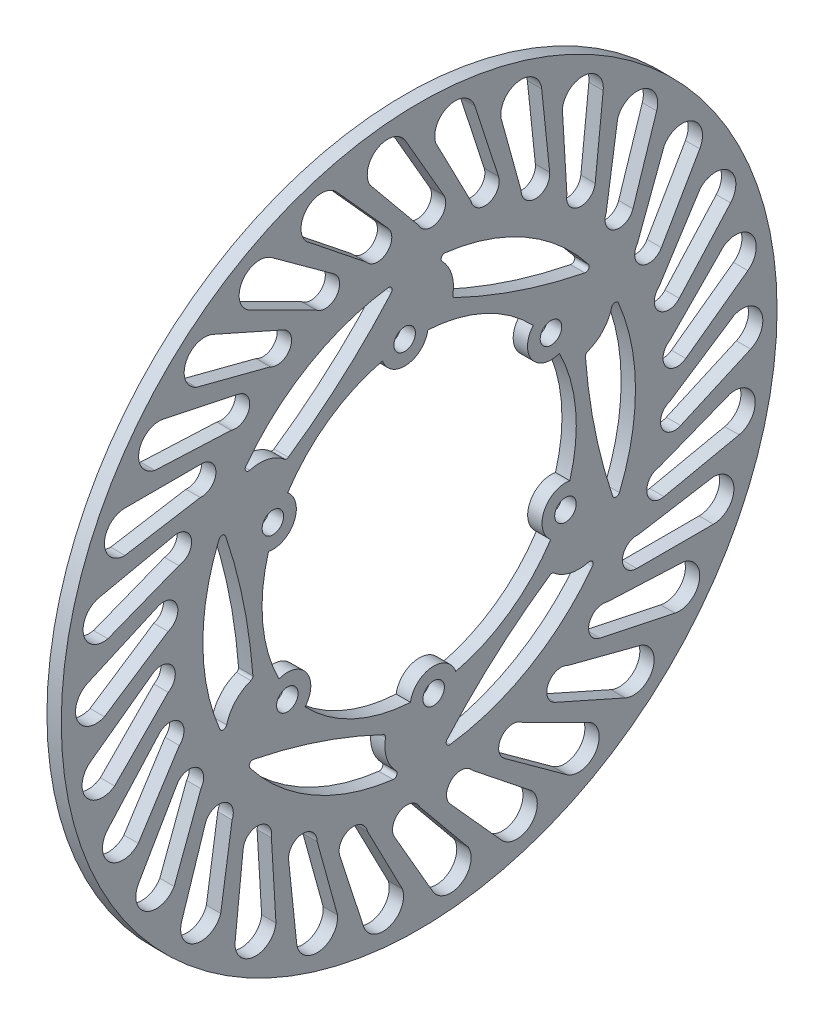
SolidWorks part; units mm, degrees
material "Gray Cast Iron"
ref_plane "Front Plane" through (0, 0, 0) normal (0, 0, 1) x (1, 0, 0)
ref_plane "Top Plane" through (0, 0, 0) normal (0, 1, 0) x (1, 0, 0)
ref_plane "Right Plane" through (0, 0, 0) normal (1, 0, 0) x (0, 0, -1)
sketch "Sketch1" plane through (0, 0, 0) normal (1, 0, 0) x (0, 0, -1)
  line L40 (68.3953, 55.3362) -> (60.9105, 35.4074)
  line L41 (78.3278, 49.6298) -> (67.626, 31.0928)
  line L42 (66.2976, 64.8306) -> (59.6837, 44.4737)
  line L43 (55.3957, 68.3472) -> (52.2179, 47.2977)
  line L44 (78.4057, 39.9067) -> (66.9411, 21.9696)
  line L45 (86.9347, 32.2599) -> (72.6128, 16.3531)
  line L46 (84.9894, 22.7332) -> (70.046, 7.5716)
  line L47 (91.7422, 13.4802) -> (74.426, 0.8987)
  line L48 (87.8586, 4.5661) -> (70.0895, -7.1572)
  line L49 (92.5401, -5.8887) -> (72.9864, -14.595)
  line L50 (86.888, -13.8006) -> (67.0698, -21.5733)
  line L51 (89.2935, -25.0002) -> (68.3569, -29.4509)
  line L52 (82.12, -31.5641) -> (61.1188, -35.0465)
  line L53 (82.1443, -43.0191) -> (60.74, -43.0196)
  line L54 (73.7629, -47.9481) -> (52.4966, -46.988)
  line L55 (71.4051, -59.1578) -> (50.4684, -54.7081)
  line L56 (62.182, -62.2365) -> (41.58, -56.8759)
  line L57 (57.5451, -72.7111) -> (37.991, -64.0056)
  line L58 (47.8834, -73.8049) -> (28.8462, -64.278)
  line L59 (41.1701, -83.0865) -> (23.8533, -70.5057)
  line L60 (31.4921, -82.1477) -> (14.8516, -68.8709)
  line L61 (22.9957, -89.8306) -> (8.6731, -73.9244)
  line L62 (13.7245, -86.9002) -> (0.208, -70.4538)
  line L63 (3.8163, -92.6487) -> (-6.8863, -74.1122)
  line L64 (-4.643, -87.8547) -> (-14.4447, -68.9575)
  line L65 (-15.5299, -91.4176) -> (-22.1446, -71.061)
  line L66 (-22.8076, -84.9696) -> (-28.4662, -64.4474)
  line L67 (-34.1973, -86.1911) -> (-36.4351, -64.9041)
  line L68 (-39.9754, -78.3708) -> (-41.2435, -57.1206)
  line L69 (-51.3702, -77.1977) -> (-49.1333, -55.9105)
  line L70 (-55.3961, -68.3469) -> (-52.2183, -47.2975)
  line L71 (-66.298, -64.8303) -> (-59.6841, -44.4734)
  line L72 (-68.3957, -55.3359) -> (-60.911, -35.4071)
  line L73 (-78.3282, -49.6295) -> (-67.6264, -31.0926)
  line L74 (-78.4061, -39.9065) -> (-66.9415, -21.9693)
  line L75 (-86.9351, -32.2597) -> (-72.6132, -16.3528)
  line L76 (-84.9898, -22.7329) -> (-70.0464, -7.5714)
  line L77 (-91.7426, -13.4799) -> (-74.4264, -0.8984)
  line L78 (-87.8591, -4.5658) -> (-70.0899, 7.1575)
  line L79 (-92.5405, 5.8889) -> (-72.9868, 14.5953)
  line L80 (-86.8884, 13.8009) -> (-67.0702, 21.5736)
  line L81 (-89.2939, 25.0005) -> (-68.3574, 29.4511)
  line L82 (-82.1204, 31.5644) -> (-61.1192, 35.0468)
  line L83 (-82.1447, 43.0193) -> (-60.7404, 43.0198)
  line L84 (-73.7633, 47.9483) -> (-52.497, 46.9882)
  line L85 (-71.4055, 59.1581) -> (-50.4688, 54.7083)
  line L86 (-62.1824, 62.2368) -> (-41.5804, 56.8761)
  line L87 (-57.5455, 72.7113) -> (-37.9914, 64.0058)
  line L88 (-47.8838, 73.8052) -> (-28.8466, 64.2783)
  line L89 (-41.1705, 83.0868) -> (-23.8537, 70.506)
  line L90 (-31.4925, 82.1479) -> (-14.8521, 68.8711)
  line L91 (-22.9961, 89.8309) -> (-8.6735, 73.9247)
  line L92 (-13.7249, 86.9004) -> (-0.2084, 70.454)
  line L93 (-3.8167, 92.649) -> (6.8858, 74.1125)
  line L94 (4.6426, 87.855) -> (14.4443, 68.9577)
  line L95 (15.5294, 91.4179) -> (22.1442, 71.0613)
  line L96 (22.8072, 84.9698) -> (28.4658, 64.4476)
  line L97 (34.1969, 86.1914) -> (36.4347, 64.9043)
  line L98 (39.975, 78.3711) -> (41.2431, 57.1209)
  line L99 (51.3698, 77.1979) -> (49.1329, 55.9108)
  circle A0 centre (0, 0) radius 99.9066
  arc A1 (42.051, -12.4701) -> (39.1395, 19.7962) centre (0, 0) ccw
  circle A2 centre (-4.0441, 44.8179) radius 3
  circle A3 centre (36.7914, 25.9112) radius 3
  circle A4 centre (40.8355, -18.9067) radius 3
  circle A5 centre (4.0441, -44.8179) radius 3
  circle A6 centre (-36.7914, -25.9112) radius 3
  circle A7 centre (-40.8355, 18.9067) radius 3
  arc A72 (67.626, 31.0928) -> (60.9105, 35.4074) centre (64.1618, 33.0843) cw
  arc A73 (78.3278, 49.6298) -> (68.3953, 55.3362) centre (73.3616, 52.483) ccw
  arc A74 (66.2976, 64.8306) -> (55.3957, 68.3472) centre (60.8466, 66.5889) ccw
  arc A75 (59.6837, 44.4737) -> (52.2179, 47.2977) centre (55.8811, 45.7014) cw
  arc A76 (72.6128, 16.3531) -> (66.9411, 21.9696) centre (69.6383, 19.0213) cw
  arc A77 (86.9347, 32.2599) -> (78.4057, 39.9067) centre (82.6702, 36.0833) ccw
  arc A78 (74.426, 0.8987) -> (70.046, 7.5716) centre (72.0712, 4.127) cw
  arc A79 (91.7422, 13.4802) -> (84.9894, 22.7332) centre (88.3658, 18.1067) ccw
  arc A80 (72.9864, -14.595) -> (70.0895, -7.1572) centre (71.3543, -10.9477) cw
  arc A81 (92.5401, -5.8887) -> (87.8586, 4.5661) centre (90.1994, -0.6613) ccw
  arc A82 (68.3569, -29.4509) -> (67.0698, -21.5733) centre (67.5189, -25.5439) cw
  arc A83 (89.2935, -25.0002) -> (86.888, -13.8006) centre (88.0908, -19.4004) ccw
  arc A84 (60.74, -43.0196) -> (61.1188, -35.0465) centre (60.7325, -39.0237) cw
  arc A85 (82.1443, -43.0191) -> (82.12, -31.5641) centre (82.1322, -37.2916) ccw
  arc A86 (50.4684, -54.7081) -> (52.4966, -46.988) centre (51.2919, -50.798) cw
  arc A87 (71.4051, -59.1578) -> (73.7629, -47.9481) centre (72.584, -53.553) ccw
  arc A88 (37.991, -64.0056) -> (41.58, -56.8759) centre (39.6095, -60.3521) cw
  arc A89 (57.5451, -72.7111) -> (62.182, -62.2365) centre (59.8635, -67.4738) ccw
  arc A90 (23.8533, -70.5057) -> (28.8462, -64.278) centre (26.196, -67.2686) cw
  arc A91 (41.1701, -83.0865) -> (47.8834, -73.8049) centre (44.5267, -78.4457) ccw
  arc A92 (8.6731, -73.9244) -> (14.8516, -68.8709) centre (11.6376, -71.2451) cw
  arc A93 (22.9957, -89.8306) -> (31.4921, -82.1477) centre (27.2439, -85.9891) ccw
  arc A94 (-6.8863, -74.1122) -> (0.208, -70.4538) centre (-3.4294, -72.1079) cw
  arc A95 (3.8163, -92.6487) -> (13.7245, -86.9002) centre (8.7704, -89.7745) ccw
  arc A96 (-22.1446, -71.061) -> (-14.4447, -68.9575) centre (-18.3466, -69.8192) cw
  arc A97 (-15.5299, -91.4176) -> (-4.643, -87.8547) centre (-10.0864, -89.6362) ccw
  arc A98 (-36.4351, -64.9041) -> (-28.4662, -64.4474) centre (-32.4619, -64.479) cw
  arc A99 (-34.1973, -86.1911) -> (-22.8076, -84.9696) centre (-28.5025, -85.5804) ccw
  arc A100 (-49.1333, -55.9105) -> (-41.2435, -57.1206) centre (-45.1585, -56.3208) cw
  arc A101 (-51.3702, -77.1977) -> (-39.9754, -78.3708) centre (-45.6728, -77.7843) ccw
  arc A102 (-59.6841, -44.4734) -> (-52.2183, -47.2975) centre (-55.8815, -45.7011) cw
  arc A103 (-66.298, -64.8303) -> (-55.3961, -68.3469) centre (-60.847, -66.5886) ccw
  arc A104 (-67.6264, -31.0926) -> (-60.911, -35.4071) centre (-64.1622, -33.0841) cw
  arc A105 (-78.3282, -49.6295) -> (-68.3957, -55.3359) centre (-73.362, -52.4827) ccw
  arc A106 (-72.6132, -16.3528) -> (-66.9415, -21.9693) centre (-69.6387, -19.0211) cw
  arc A107 (-86.9351, -32.2597) -> (-78.4061, -39.9065) centre (-82.6706, -36.0831) ccw
  arc A108 (-74.4264, -0.8984) -> (-70.0464, -7.5714) centre (-72.0717, -4.1268) cw
  arc A109 (-91.7426, -13.4799) -> (-84.9898, -22.7329) centre (-88.3662, -18.1064) ccw
  arc A110 (-72.9868, 14.5953) -> (-70.0899, 7.1575) centre (-71.3547, 10.9479) cw
  arc A111 (-92.5405, 5.8889) -> (-87.8591, -4.5658) centre (-90.1998, 0.6616) ccw
  arc A112 (-68.3574, 29.4511) -> (-67.0702, 21.5736) centre (-67.5193, 25.5441) cw
  arc A113 (-89.2939, 25.0005) -> (-86.8884, 13.8009) centre (-88.0912, 19.4007) ccw
  arc A114 (-60.7404, 43.0198) -> (-61.1192, 35.0468) centre (-60.733, 39.0239) cw
  arc A115 (-82.1447, 43.0193) -> (-82.1204, 31.5644) centre (-82.1326, 37.2919) ccw
  arc A116 (-50.4688, 54.7083) -> (-52.497, 46.9882) centre (-51.2923, 50.7982) cw
  arc A117 (-71.4055, 59.1581) -> (-73.7633, 47.9483) centre (-72.5844, 53.5532) ccw
  arc A118 (-37.9914, 64.0058) -> (-41.5804, 56.8761) centre (-39.6099, 60.3524) cw
  arc A119 (-57.5455, 72.7113) -> (-62.1824, 62.2368) centre (-59.8639, 67.4741) ccw
  arc A144 (42.051, -12.4701) -> (36.7137, -23.9977) centre (40.8355, -18.9067) ccw
  arc A145 (10.226, -42.6523) -> (-2.4257, -43.7939) centre (4.0441, -44.8179) ccw
  arc A146 (-31.8249, -30.1821) -> (-39.1395, -19.7962) centre (-36.7914, -25.9112) ccw
  arc A147 (-42.051, 12.4701) -> (-36.7137, 23.9977) centre (-40.8355, 18.9067) ccw
  arc A148 (-10.226, 42.6523) -> (2.4257, 43.7939) centre (-4.0441, 44.8179) ccw
  arc A149 (31.8249, 30.1821) -> (39.1395, 19.7962) centre (36.7914, 25.9112) ccw
  arc A150 (10.226, -42.6523) -> (36.7137, -23.9977) centre (0, 0) ccw
  arc A151 (-31.8249, -30.1821) -> (-2.4257, -43.7939) centre (0, 0) ccw
  arc A152 (-42.051, 12.4701) -> (-39.1395, -19.7962) centre (0, 0) ccw
  arc A153 (-10.226, 42.6523) -> (-36.7137, 23.9977) centre (0, 0) ccw
  arc A154 (31.8249, 30.1821) -> (2.4257, 43.7939) centre (0, 0) ccw
  arc A155 (-23.8537, 70.506) -> (-28.8466, 64.2783) centre (-26.1964, 67.2689) cw
  arc A156 (-41.1705, 83.0868) -> (-47.8838, 73.8052) centre (-44.5272, 78.446) ccw
  arc A157 (-8.6735, 73.9247) -> (-14.8521, 68.8711) centre (-11.638, 71.2454) cw
  arc A158 (-22.9961, 89.8309) -> (-31.4925, 82.1479) centre (-27.2443, 85.9894) ccw
  arc A159 (6.8858, 74.1125) -> (-0.2084, 70.454) centre (3.429, 72.1081) cw
  arc A160 (-3.8167, 92.649) -> (-13.7249, 86.9004) centre (-8.7708, 89.7747) ccw
  arc A161 (22.1442, 71.0613) -> (14.4443, 68.9577) centre (18.3462, 69.8194) cw
  arc A162 (15.5294, 91.4179) -> (4.6426, 87.855) centre (10.086, 89.6364) ccw
  arc A163 (36.4347, 64.9043) -> (28.4658, 64.4476) centre (32.4615, 64.4793) cw
  arc A168 (34.1969, 86.1914) -> (22.8072, 84.9698) centre (28.5021, 85.5806) ccw
  arc A173 (49.1329, 55.9108) -> (41.2431, 57.1209) centre (45.1581, 56.3211) cw
  arc A178 (51.3698, 77.1979) -> (39.975, 78.3711) centre (45.6724, 77.7845) ccw
  arc A200 (-7.7896, 57.8859) -> (-36.5325, 32.4972) centre (-123.3086, 159.7023) cw
  arc A201 (-47.3041, 34.7453) -> (-37.5781, 32.5523) centre (-44.5369, 24.3543) cw
  arc A202 (-8.6724, 59.5383) -> (-48.3606, 36.3128) centre (-0.7718, 0.515) ccw
  arc A211 (-36.5325, 32.4972) -> (-37.5781, 32.5523) centre (-37.0192, 33.2107) cw
  arc A230 (-48.3606, 36.3128) -> (-47.3041, 34.7453) centre (-47.5615, 35.7116) ccw
  arc A231 (-8.6724, 59.5383) -> (-7.7896, 57.8859) centre (-8.5398, 58.5472) cw
  arc A232 (46.2359, 35.6889) -> (9.8772, 47.8867) centre (76.6519, 186.6396) cw
  arc A233 (47.2255, 37.2797) -> (46.2359, 35.6889) centre (46.4334, 36.6692) cw
  arc A234 (9.8772, 47.8867) -> (9.402, 48.8197) centre (10.2517, 48.6649) cw
  arc A235 (6.4383, 58.3392) -> (9.402, 48.8197) centre (-1.177, 50.7472) cw
  arc A236 (7.2675, 60.0379) -> (6.4383, 58.3392) centre (7.1465, 59.0453) ccw
  arc A237 (47.2255, 37.2797) -> (7.2675, 60.0379) centre (0.0601, 0.9259) ccw
  arc A238 (54.0255, -22.197) -> (46.4097, 15.3894) centre (199.9605, 26.9373) cw
  arc A239 (55.8979, -22.2586) -> (54.0255, -22.197) centre (54.9732, -21.8779) cw
  arc A240 (46.4097, 15.3894) -> (46.9801, 16.2674) centre (47.2709, 15.4542) cw
  arc A241 (53.7424, 23.5939) -> (46.9801, 16.2674) centre (43.3598, 26.3929) cw
  arc A242 (55.6281, 23.7251) -> (53.7424, 23.5939) centre (54.7079, 23.3336) ccw
  arc A243 (55.8979, -22.2586) -> (55.6281, 23.7251) centre (0.8319, 0.4109) ccw
  arc A244 (7.7896, -57.8859) -> (36.5325, -32.4972) centre (123.3086, -159.7023) cw
  arc A245 (8.6724, -59.5383) -> (7.7896, -57.8859) centre (8.5398, -58.5472) cw
  arc A246 (36.5325, -32.4972) -> (37.5781, -32.5523) centre (37.0192, -33.2107) cw
  arc A247 (47.3041, -34.7453) -> (37.5781, -32.5523) centre (44.5369, -24.3543) cw
  arc A248 (48.3606, -36.3128) -> (47.3041, -34.7453) centre (47.5615, -35.7116) ccw
  arc A249 (8.6724, -59.5383) -> (48.3606, -36.3128) centre (0.7718, -0.515) ccw
  arc A250 (-46.2359, -35.6889) -> (-9.8772, -47.8867) centre (-76.6519, -186.6396) cw
  arc A251 (-47.2255, -37.2797) -> (-46.2359, -35.6889) centre (-46.4334, -36.6692) cw
  arc A252 (-9.8772, -47.8867) -> (-9.402, -48.8197) centre (-10.2517, -48.6649) cw
  arc A253 (-6.4383, -58.3392) -> (-9.402, -48.8197) centre (1.177, -50.7472) cw
  arc A254 (-7.2675, -60.0379) -> (-6.4383, -58.3392) centre (-7.1465, -59.0453) ccw
  arc A255 (-47.2255, -37.2797) -> (-7.2675, -60.0379) centre (-0.0601, -0.9259) ccw
  arc A256 (-54.0255, 22.197) -> (-46.4097, -15.3894) centre (-199.9605, -26.9373) cw
  arc A257 (-55.8979, 22.2586) -> (-54.0255, 22.197) centre (-54.9732, 21.8779) cw
  arc A258 (-46.4097, -15.3894) -> (-46.9801, -16.2674) centre (-47.2709, -15.4542) cw
  arc A259 (-53.7424, -23.5939) -> (-46.9801, -16.2674) centre (-43.3598, -26.3929) cw
  arc A260 (-55.6281, -23.7251) -> (-53.7424, -23.5939) centre (-54.7079, -23.3336) ccw
  arc A261 (-55.8979, 22.2586) -> (-55.6281, -23.7251) centre (-0.8319, -0.4109) ccw
  point P19 (0, 0)
  point P139 (0, 0)
  point P188 (-0.3692, -0.1118)
  point P213 (-0.0002, 0.0001)
  point P215 (0, 0)
  point P238 (0, 0)
  point P274 (0, 0)
  point P321 (0, 0)
  dimension "D1" = 6
  dimension "D4" = 6
  dimension "D7" = 6
  dimension "D3" = 1
  dimension "D2" = 30
extrude "Boss-Extrude1" add sketch "Sketch1" along normal mid plane 4
ref_plane "Plane1" through (0, 0, 0) normal (1, 0, 0) x (0, 0, -1)
